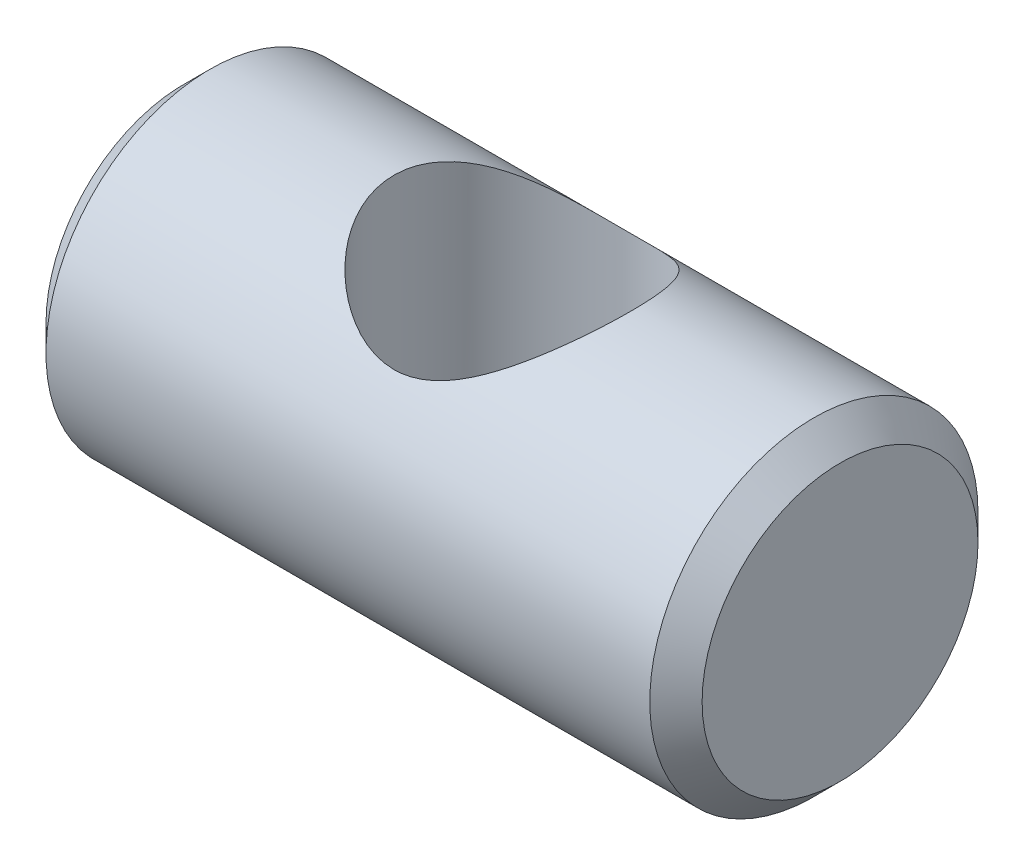
SolidWorks part; units mm, degrees
ref_plane "Front Plane" through (0, 0, 0) normal (0, 0, 1) x (1, 0, 0)
ref_plane "Top Plane" through (0, 0, 0) normal (0, 1, 0) x (1, 0, 0)
ref_plane "Right Plane" through (0, 0, 0) normal (1, 0, 0) x (0, 0, -1)
sketch "Sketch1" plane through (0, 0, 0) normal (1, 0, 0) x (0, 0, -1)
  circle A0 centre (0, 0) radius 4.765
extrude "Boss-Extrude1" add sketch "Sketch1" along normal blind 19.05
chamfer "Chamfer1" distance 0.76 angle 45 2 edges at (0, 0, -4.765) (19.05, 0, -4.765)
sketch "Sketch2" plane through (0, 0, 0) normal (0, 1, 0) x (1, 0, 0)
  circle A0 centre (9.525, 0) radius 3.43
  point P5 (0, 0)
extrude "Cut-Extrude1" cut sketch "Sketch2" against normal through all both and the other way through all
